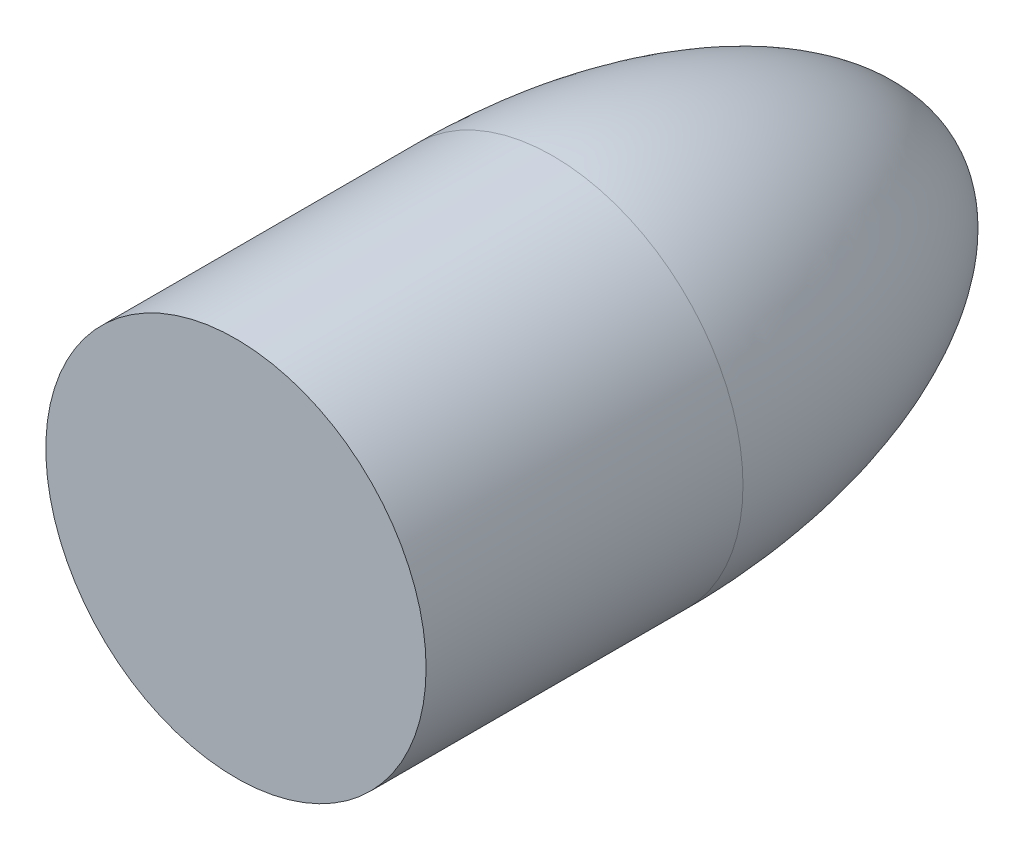
SolidWorks part; units mm, degrees
other "Markup1"
sketch "Sketch3" plane through (-76.2, 76.2, -762) normal (-0.6807, 0.6563, -0.3256) x (-0.115, 0.3432, 0.9322)
sketch "Sketch4" plane through (-76.2, 76.2, -152.4) normal (-0.6807, 0.6563, -0.3256) x (-0.115, 0.3432, 0.9322)
sketch "Sketch5" plane through (-76.2, 76.2, -152.4) normal (-0.6807, 0.6563, -0.3256) x (-0.115, 0.3432, 0.9322)
ref_plane "Front Plane" through (0, 0, 0) normal (0, 0, 1) x (1, 0, 0)
ref_plane "Top Plane" through (0, 0, 0) normal (0, 1, 0) x (1, 0, 0)
ref_plane "Right Plane"
sketch "Sketch1" plane through (0, 0, 0) normal (1, 0, 0) x (0, 0, -1)
  line L0 (0, 76.2) -> (0, 0)
  line L1 (0, 0) -> (152.4, 0)
  spline S0 degree 4 poles (-15.24, 75.818) (-14.7642, 75.842) (-13.8124, 75.8878) (-12.3843, 75.9505) (-10.4802, 76.0221) (-8.5743, 76.0818) (-6.6724, 76.1295) (-4.7531, 76.1652) (-2.9047, 76.1891) (-0.529, 76.2025) (1.1022, 76.2003) (3.3476, 76.1851) (5.3899, 76.1542) (7.6149, 76.1095) (10.117, 76.0373) (13.0245, 75.9272) (15.9071, 75.7894) (18.8006, 75.6239) (22.4078, 75.382) (26.7366, 75.0358) (31.0567, 74.6188) (35.3709, 74.13) (38.9593, 73.6743) (41.8265, 73.2803) (45.405, 72.7507) (49.6901, 72.0552) (56.0983, 70.8973) (63.1784, 69.4014) (70.2088, 67.6864) (78.5714, 65.3499) (86.8489, 62.7231) (96.3539, 59.2054) (106.4246, 54.7218) (114.8783, 50.2217) (121.7743, 45.9222) (127.2123, 42.0475) (131.7286, 38.422) (136.0013, 34.5107) (139.7022, 30.5826) (142.7865, 26.757) (145.2956, 23.1058) (147.2898, 19.6987) (148.9788, 16.2246) (150.3352, 12.7151) (151.3506, 9.2076) (152.061, 5.5827) (152.3344, 2.8677) (152.4, 1.0073) (152.4, 0) knots 0 0 0 0 0 0.009538 0.019076 0.028614 0.038152 0.04769 0.057228 0.066766 0.076304 0.090787 0.098029 0.105271 0.119755 0.134238 0.148722 0.163205 0.177689 0.192172 0.22114 0.250107 0.26459 0.279074 0.293557 0.308041 0.337008 0.365975 0.423909 0.452877 0.481844 0.539778 0.597712 0.655646 0.702351 0.731318 0.760285 0.789253 0.818219 0.847186 0.868214 0.887525 0.906834 0.926145 0.945461 0.962753 0.979837 1 1 1 1 1 construction
  spline S1 degree 4 poles (0, 76.2) (0.6683, 76.2) (1.6584, 76.1966) (3.3476, 76.1851) (5.3899, 76.1542) (7.6149, 76.1095) (10.117, 76.0373) (13.0245, 75.9272) (15.9071, 75.7894) (18.8006, 75.6239) (22.4078, 75.382) (26.7366, 75.0358) (31.0567, 74.6188) (35.3709, 74.13) (38.9593, 73.6743) (41.8265, 73.2803) (45.405, 72.7507) (49.6901, 72.0552) (56.0983, 70.8973) (63.1784, 69.4014) (70.2088, 67.6864) (78.5714, 65.3499) (86.8489, 62.7231) (96.3539, 59.2054) (106.4246, 54.7218) (114.8783, 50.2217) (121.7743, 45.9222) (127.2123, 42.0475) (131.7286, 38.422) (136.0013, 34.5107) (139.7022, 30.5826) (142.7865, 26.757) (145.2956, 23.1058) (147.2898, 19.6987) (148.9788, 16.2246) (150.3352, 12.7151) (151.3506, 9.2076) (152.061, 5.5827) (152.3344, 2.8677) (152.4, 1.0073) (152.4, 0) knots 0.076304 0.076304 0.076304 0.076304 0.076304 0.090787 0.098029 0.105271 0.119755 0.134238 0.148722 0.163205 0.177689 0.192172 0.22114 0.250107 0.26459 0.279074 0.293557 0.308041 0.337008 0.365975 0.423909 0.452877 0.481844 0.539778 0.597712 0.655646 0.702351 0.731318 0.760285 0.789253 0.818219 0.847186 0.868214 0.887525 0.906834 0.926145 0.945461 0.962753 0.979837 1 1 1 1 1
ref_axis "Axis1" through (0, 0, -480.06) along (0, 0, 1)
revolve "Revolve1" add sketch "Sketch1" angle 360 about axis through (0, 0, -480.06) along (0, 0, 1)
sketch "Sketch2" plane through (0, 0, 0) normal (0, 0, 1) x (1, 0, 0)
  circle A0 centre (0, 0) radius 76.2
  dimension "D1" = 152.4
extrude "Boss-Extrude1" add sketch "Sketch2" along normal blind 127
equation "\"BodyTubeRadius\"= 3in"
equation "\"ratio\"= 1"
equation "\"NoseConeLength\"= \"ratio\" * 2 * \"BodyTubeRadius\""
equation "\"D1@Sketch2\"=2*\"BodyTubeRadius\""
equation "\"BodyTubeLength\"=5"
